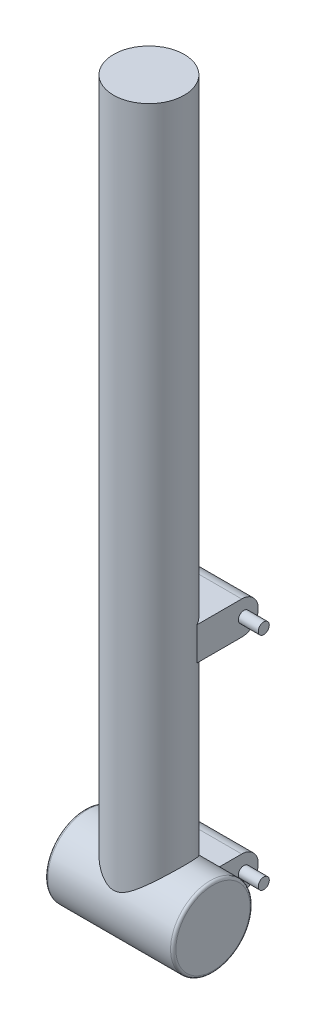
SolidWorks part; units mm, degrees
ref_plane "Plan de face" through (0, 0, 0) normal (0, 0, 1) x (1, 0, 0)
ref_plane "Plan de dessus" through (0, 0, 0) normal (0, 1, 0) x (1, 0, 0)
ref_plane "Plan de droite" through (0, 0, 0) normal (1, 0, 0) x (0, 0, -1)
sketch "Esquisse2" plane through (0, 0, 0) normal (1, 0, 0) x (0, 0, -1)
  circle A0 centre (0, 0) radius 180
  dimension "D1" = 360
extrude "Boss.-Extru.1" add sketch "Esquisse2" along normal mid plane 580
fillet "Congé1" radius 12 2 edges at (-290, 0, -180) (290, 0, -180)
sketch "Esquisse3" plane through (0, 0, 0) normal (0, 1, 0) x (1, 0, 0)
  circle A0 centre (0, 0) radius 160
  dimension "D1" = 320
extrude "Boss.-Extru.2" add sketch "Esquisse3" along normal blind 3200
sketch "Esquisse4" plane through (0, 0, 0) normal (1, 0, 0) x (0, 0, -1)
  line L0 (0, 75) -> (280, 75)
  line L1 (0, -75) -> (280, -75)
  line L2 (140, 75) -> (140, -75) construction
  arc A0 (0, 75) -> (0, -75) centre (0, 0) ccw
  arc A1 (280, 75) -> (280, -75) centre (280, 0) cw
  dimension "D1" = 150
  dimension "D2" = 140
extrude "Boss.-Extru.3" add sketch "Esquisse4" along normal mid plane 280
sketch "Esquisse5" plane through (140, 0, 0) normal (1, 0, 0) x (0, 0, -1)
  circle A0 centre (289.9589, 0) radius 25
  arc A1 (280, -75) -> (280, 75) centre (280, 0) ccw construction
  arc A2 (280, -75) -> (280, 75) centre (280, 0) ccw construction
  dimension "D1" = 50
extrude "Boss.-Extru.4" add sketch "Esquisse5" along normal blind 90
mirror "Symétrie1" about plane through (0, 0, 0) normal (1, 0, 0) of "Boss.-Extru.4"
pattern_linear "Répétition linéaire2" count 2 spacing 1000 along (0, 1, 0) of "Boss.-Extru.4", "Symétrie1", "Boss.-Extru.3"
sketch "Esquisse6" plane through (0, 0, 0) normal (1, 0, 0) x (0, 0, -1)
  line L0 (0, 1350) -> (0, 1650)
  line L1 (0, 1650) -> (-500, 1500)
  line L2 (-500, 1500) -> (0, 1350)
  line L3 (0, 1500) -> (-1012.3297, 1500) construction
  point P6 (-506.1648, 1705.0553)
  point P7 (0, 0)
  point P8 (0, 0)
  dimension "D1" = 1350
  dimension "D2" = 300
  dimension "D3" = 500
